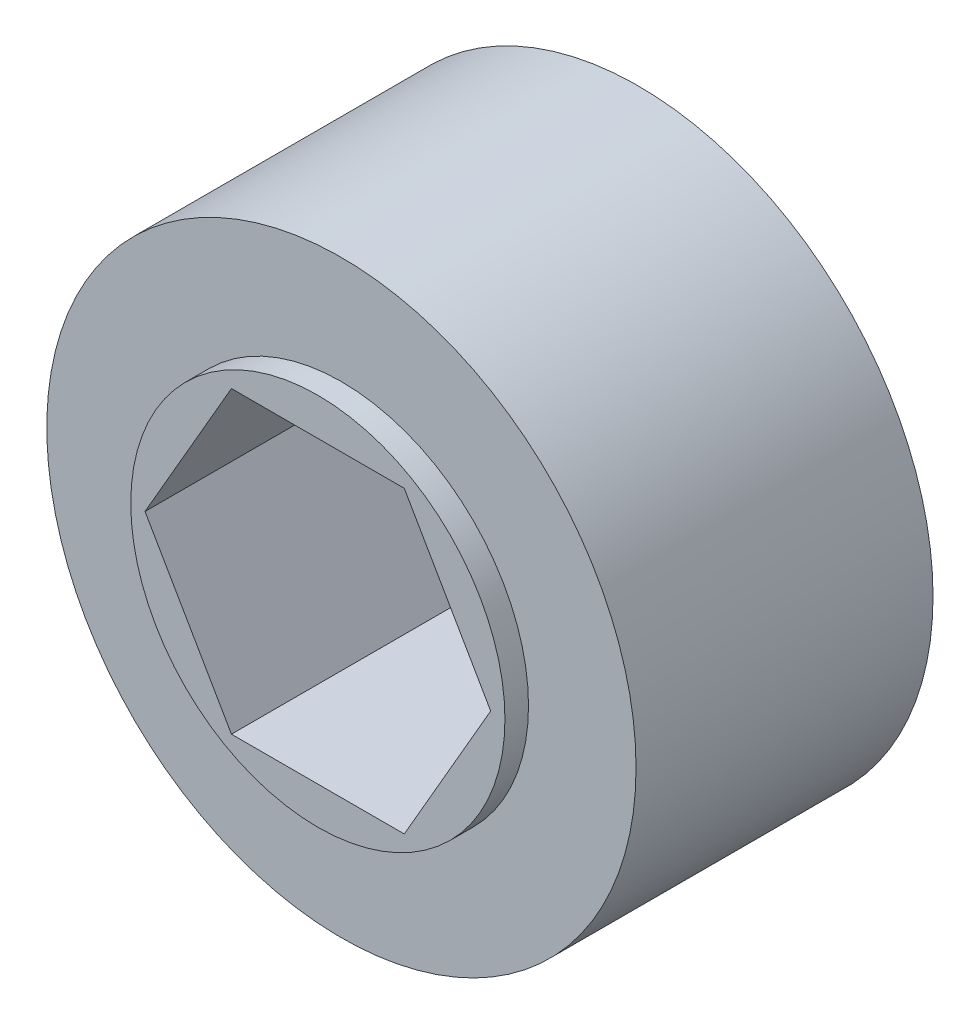
SolidWorks part; units mm, degrees
ref_plane "Front Plane" through (0, 0, 0) normal (0, 0, 1) x (1, 0, 0)
ref_plane "Top Plane" through (0, 0, 0) normal (0, 1, 0) x (1, 0, 0)
ref_plane "Right Plane" through (0, 0, 0) normal (1, 0, 0) x (0, 0, -1)
other "Default"
sketch "Sketch1" plane through (0, 0, 0) normal (0, 0, 1) x (1, 0, 0)
  line L1 (7.3323, 0) -> (3.6662, 6.35)
  line L2 (3.6662, 6.35) -> (-3.6662, 6.35)
  line L3 (-3.6662, 6.35) -> (-7.3323, 0)
  line L4 (-7.3323, 0) -> (-3.6662, -6.35)
  line L5 (-3.6662, -6.35) -> (3.6662, -6.35)
  line L6 (3.6662, -6.35) -> (7.3323, 0)
  circle A0 centre (0, 0) radius 12.5
  circle A1 centre (0, 0) radius 6.35 construction
  dimension "D2" = 25
  dimension "D1" = 12.7
extrude "Boss-Extrude1" add sketch "Sketch1" along normal mid plane 13.6
sketch "Sketch2" plane through (0, 0, 6.8) normal (0, 0, 1) x (1, 0, 0)
  circle A0 centre (0, 0) radius 7.9375
  circle A2 centre (0, 0) radius 12.5 construction
  circle A3 centre (0, 0) radius 12.5
  dimension "D1" = 15.875
extrude "Cut-Extrude1" cut sketch "Sketch2" against normal blind 1
